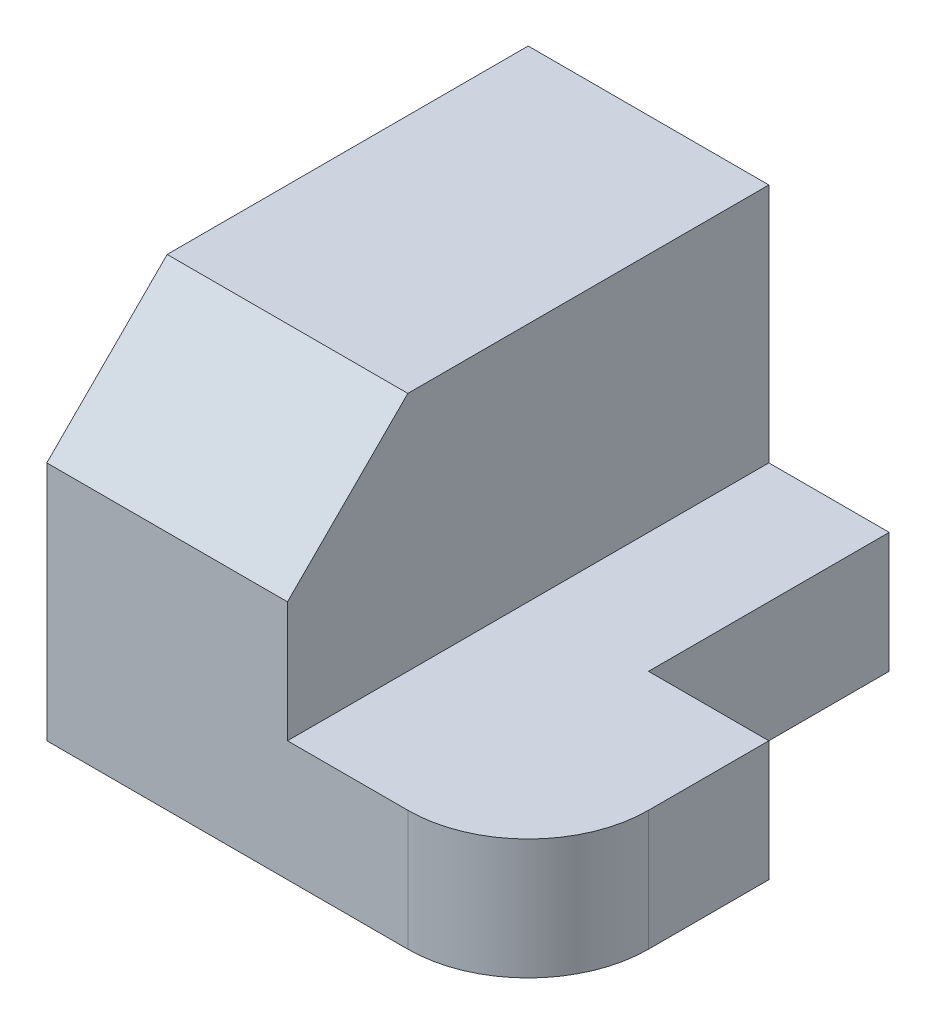
SolidWorks part; units mm, degrees
ref_plane "Front Plane" through (0, 0, 0) normal (0, 0, 1) x (1, 0, 0)
ref_plane "Top Plane" through (0, 0, 0) normal (0, 1, 0) x (1, 0, 0)
ref_plane "Right Plane" through (0, 0, 0) normal (1, 0, 0) x (0, 0, -1)
sketch "Sketch2" plane through (0, 0, 0) normal (0, 1, 0) x (1, 0, 0)
  line L0 (-43.7607, 14.359) -> (-43.7607, -25.641)
  line L1 (-43.7607, -25.641) -> (-13.7607, -25.641)
  line L2 (-3.7607, -15.641) -> (-3.7607, -5.641)
  line L3 (-3.7607, -5.641) -> (-13.7607, -5.641)
  line L4 (-13.7607, -5.641) -> (-13.7607, 14.359)
  line L5 (-13.7607, 14.359) -> (-43.7607, 14.359)
  arc A0 (-13.7607, -25.641) -> (-3.7607, -15.641) centre (-13.7607, -15.641) ccw
  point P8 (-3.7607, -25.641)
  dimension "D5" = 10
  dimension "D1" = 40
  dimension "D2" = 30
  dimension "D3" = 20
  dimension "D4" = 40
extrude "Boss-Extrude1" add sketch "Sketch2" along normal blind 30 contours L1 A0 L2 L3 L4 L5 L0
sketch "Sketch3" plane through (0, 30, 0) normal (0, 1, 0) x (1, 0, 0)
  line L0 (-43.7607, -25.641) -> (-13.7607, -25.641) construction
  line L1 (-43.7607, 14.359) -> (-23.7607, 14.359)
  line L2 (-43.7607, 14.359) -> (-43.7607, -25.641)
  line L3 (-43.7607, -25.641) -> (-23.7607, -25.641)
  line L4 (-23.7607, 14.359) -> (-23.7607, -25.641)
  dimension "D1" = 20
extrude "Cut-Extrude1" cut sketch "Sketch3" against normal blind 20 flip side to cut
sketch "Sketch4" plane through (-43.7607, 0, 0) normal (-1, 0, 0) x (0, 0, 1)
  line L0 (15.641, 30) -> (25.641, 20)
  line L1 (-14.359, 30) -> (25.641, 30) construction
  line L2 (25.641, 30) -> (25.641, 0) construction
  line L3 (15.641, 30) -> (25.641, 30)
  line L4 (25.641, 30) -> (25.641, 20)
  dimension "D1" = 10
  dimension "D2" = 45
extrude "Cut-Extrude2" cut sketch "Sketch4" against normal blind 20 contours L4 L0 L3
